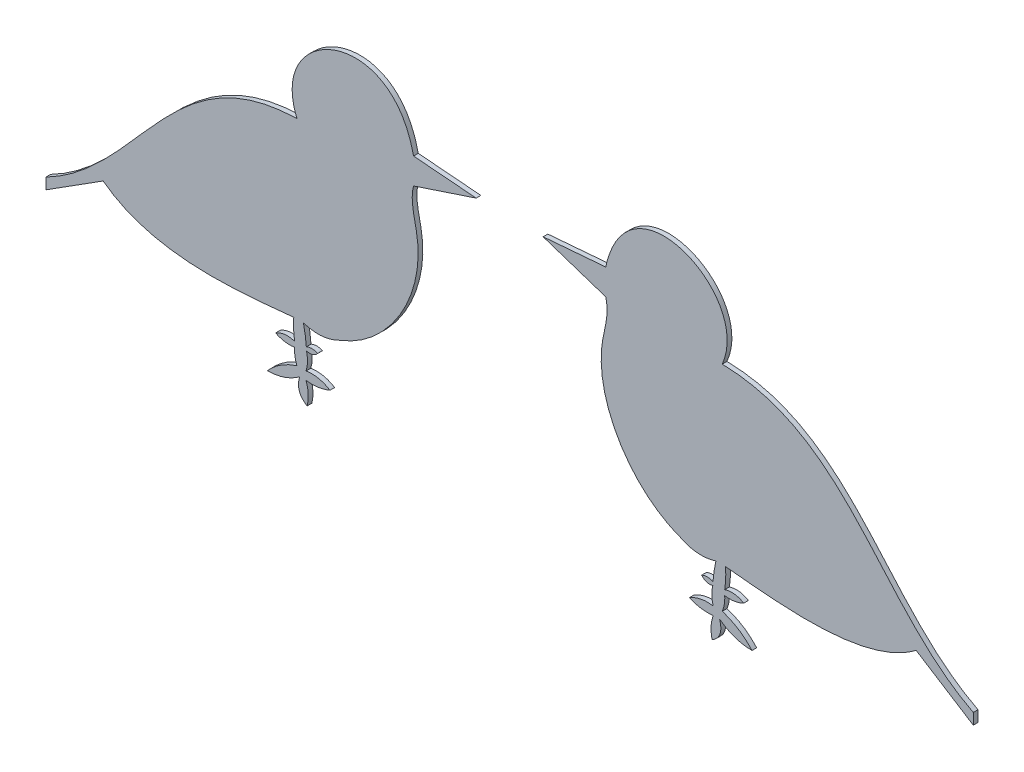
SolidWorks part; units mm, degrees
ref_plane "Front Plane" through (0, 0, 0) normal (0, 0, 1) x (1, 0, 0)
ref_plane "Top Plane" through (0, 0, 0) normal (0, 1, 0) x (1, 0, 0)
ref_plane "Right Plane" through (0, 0, 0) normal (1, 0, 0) x (0, 0, -1)
sketch "Sketch1" plane through (0, 0, 0) normal (0, 0, 1) x (1, 0, 0)
  line L0 (39.7259, 114.1075) -> (197.0592, 114.1075) construction
  line L1 (87.1139, 154.0279) -> (129.4204, 150.5621)
  line L2 (129.4204, 150.5621) -> (87.1139, 136.5409)
  line L3 (-161.4504, 17.4604) -> (-161.4504, 9.9707)
  line L4 (152.0701, 189.7538) -> (152.0701, -8.1748) construction
  line L5 (465.5906, 9.9707) -> (426.9507, 34.4719)
  line L6 (-161.4504, 9.9707) -> (-122.8104, 34.4719)
  line L7 (465.5906, 17.4604) -> (465.5906, 9.9707)
  line L8 (174.7199, 150.5621) -> (217.0263, 136.5409)
  line L9 (217.0263, 154.0279) -> (174.7199, 150.5621)
  spline S0 degree 3 poles (8.2867, 136.5409) (-76.9422, 134.6829) (-97.6329, 50.1164) (-161.4504, 17.4604) knots 0 0 0 0 1 1 1 1
  spline S1 degree 3 poles (87.1139, 154.0279) (71.9999, 223.2109) (-12.6164, 185.3481) (8.2867, 136.5409) knots 0 0 0 0 1 1 1 1
  spline S2 degree 3 poles (-122.8104, 34.4719) (-87.9542, 8.0682) (-30.5486, 15.5869) (6.0974, 19.1) knots 0 0 0 0 1 1 1 1
  spline S3 degree 2 poles (6.0974, 19.1) (5.5651, 12.128) (6.6626, 5.2715) knots 0 0 0 1 1 1
  spline S4 degree 2 poles (8.2867, -8.1748) (-3.5975, -11.9478) (-11.8264, -21.09) knots 0 0 0 1 1 1
  spline S5 degree 2 poles (-11.8264, -21.09) (0.1076, -21.0502) (10.0961, -13.7368) knots 0 0 0 1 1 1
  spline S6 degree 2 poles (10.0961, -13.7368) (7.0841, -23.4156) (15.1274, -28.2777) knots 0 0 0 1 1 1
  spline S7 degree 2 poles (15.1274, -28.2777) (16.9451, -21.016) (14.4087, -13.7368) knots 0 0 0 1 1 1
  spline S8 degree 2 poles (14.4087, -13.7368) (22.7776, -14.7021) (30.581, -11.3867) knots 0 0 0 1 1 1
  spline S9 degree 2 poles (30.581, -11.3867) (23.0549, -6.7678) (14.4087, -8.1748) knots 0 0 0 1 1 1
  spline S10 degree 2 poles (14.5681, 6.0395) (14.0955, 12.592) (12.6117, 19.1) knots 0.51939 0.51939 0.51939 1 1 1
  spline S11 degree 2 poles (12.6117, 19.1) (25.4117, 15.0701) (37.2374, 21.2229) knots 0 0 0 1 1 1
  spline S12 degree 2 poles (6.6626, 5.2715) (-0.1081, 7.5016) (-6.1822, 3.7951) knots 0 0 0 1 1 1
  spline S13 degree 2 poles (-6.1822, 3.7951) (-0.079, 0.7709) (6.6626, 1.7959) knots 0 0 0 1 1 1
  spline S14 degree 2 poles (6.6626, 1.7959) (6.3087, -3.4298) (8.2867, -8.1748) knots 0 0 0 1 1 1
  spline S15 degree 2 poles (14.5681, 6.0395) (18.4972, 7.8445) (22.2398, 6.0097) knots 0 0 0 1 1 1
  spline S16 degree 2 poles (22.2398, 6.0097) (19.2676, 2.523) (14.7066, 3.6542) knots 0 0 0 1 1 1
  spline S17 degree 2 poles (14.4087, -8.1748) (16.1949, -2.2975) (14.7066, 3.6542) knots 0 0 0 1 1 1
  spline S18 degree 3 poles (37.2374, 21.2229) (70.1131, 33.5211) (101.3312, 83.3592) (84.5035, 127.0884) (87.1139, 136.5409) knots 0 0 0 0 0.790174 1 1 1 1
  spline S19 degree 3 poles (266.9028, 21.2229) (234.0272, 33.5211) (202.809, 83.3592) (219.6367, 127.0884) (217.0263, 136.5409) knots 0 0 0 0 0.790174 1 1 1 1
  spline S20 degree 2 poles (289.7316, -8.1748) (287.9453, -2.2975) (289.4336, 3.6542) knots 0 0 0 1 1 1
  spline S21 degree 2 poles (281.9005, 6.0097) (284.8726, 2.523) (289.4336, 3.6542) knots 0 0 0 1 1 1
  spline S22 degree 2 poles (289.5721, 6.0395) (285.6431, 7.8445) (281.9005, 6.0097) knots 0 0 0 1 1 1
  spline S23 degree 2 poles (297.4776, 1.7959) (297.8315, -3.4298) (295.8535, -8.1748) knots 0 0 0 1 1 1
  spline S24 degree 2 poles (310.3224, 3.7951) (304.2192, 0.7709) (297.4776, 1.7959) knots 0 0 0 1 1 1
  spline S25 degree 2 poles (297.4776, 5.2715) (304.2483, 7.5016) (310.3224, 3.7951) knots 0 0 0 1 1 1
  spline S26 degree 2 poles (291.5285, 19.1) (278.7286, 15.0701) (266.9028, 21.2229) knots 0 0 0 1 1 1
  spline S27 degree 2 poles (289.5721, 6.0395) (290.0447, 12.592) (291.5285, 19.1) knots 0.51939 0.51939 0.51939 1 1 1
  spline S28 degree 2 poles (273.5593, -11.3867) (281.0854, -6.7678) (289.7316, -8.1748) knots 0 0 0 1 1 1
  spline S29 degree 2 poles (289.7316, -13.7368) (281.3626, -14.7021) (273.5593, -11.3867) knots 0 0 0 1 1 1
  spline S30 degree 2 poles (289.0128, -28.2777) (287.1951, -21.016) (289.7316, -13.7368) knots 0 0 0 1 1 1
  spline S31 degree 2 poles (294.0442, -13.7368) (297.0561, -23.4156) (289.0128, -28.2777) knots 0 0 0 1 1 1
  spline S32 degree 2 poles (315.9666, -21.09) (304.0326, -21.0502) (294.0442, -13.7368) knots 0 0 0 1 1 1
  spline S33 degree 2 poles (295.8535, -8.1748) (307.7377, -11.9478) (315.9666, -21.09) knots 0 0 0 1 1 1
  spline S34 degree 2 poles (298.0429, 19.1) (298.5752, 12.128) (297.4776, 5.2715) knots 0 0 0 1 1 1
  spline S35 degree 3 poles (426.9507, 34.4719) (392.0944, 8.0682) (334.6889, 15.5869) (298.0429, 19.1) knots 0 0 0 0 1 1 1 1
  spline S36 degree 3 poles (217.0263, 154.0279) (232.1403, 223.2109) (316.7566, 185.3481) (295.8535, 136.5409) knots 0 0 0 0 1 1 1 1
  spline S37 degree 3 poles (295.8535, 136.5409) (381.0824, 134.6829) (401.7731, 50.1164) (465.5906, 17.4604) knots 0 0 0 0 1 1 1 1
extrude "Boss-Extrude1" add sketch "Sketch1" along normal blind 3.175
